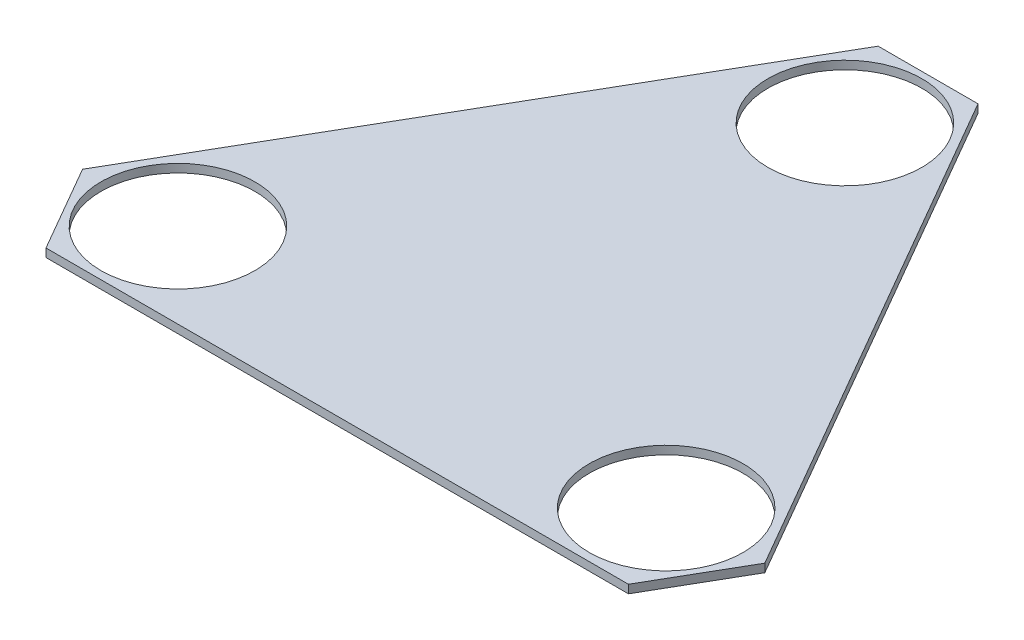
SolidWorks part; units mm, degrees
material "自定义塑料"
ref_plane "前视基准面" through (0, 0, 0) normal (0, 0, 1) x (1, 0, 0)
ref_plane "上视基准面" through (0, 0, 0) normal (0, 1, 0) x (1, 0, 0)
ref_plane "右视基准面" through (0, 0, 0) normal (1, 0, 0) x (0, 0, -1)
sketch "草图1" plane through (0, 0, 0) normal (0, 1, 0) x (1, 0, 0)
  line L0 (0, 0) -> (700, 0)
  line L1 (700, 0) -> (760, 103.923)
  line L2 (760, 103.923) -> (410, 710.1408)
  line L3 (410, 710.1408) -> (290, 710.1408)
  line L4 (290, 710.1408) -> (-60, 103.923)
  line L5 (-60, 103.923) -> (0, 0)
extrude "凸台-拉伸1" add sketch "草图1" along normal blind 10
sketch "草图2" plane through (0, 10, 0) normal (0, 1, 0) x (1, 0, 0)
  line L0 (-30, 51.9615) -> (56.6025, 101.9615)
  line L1 (-60, 103.923) -> (0, 0) construction
  line L2 (730, 51.9615) -> (643.3975, 101.9615)
  line L3 (700, 0) -> (760, 103.923) construction
  line L4 (350, 710.1408) -> (350, 610.1408)
  line L5 (410, 710.1408) -> (290, 710.1408) construction
  circle A0 centre (56.6025, 101.9615) radius 92.5
  circle A1 centre (643.3975, 101.9615) radius 92.5
  circle A2 centre (350, 610.1408) radius 92.5
extrude "切除-拉伸1" cut sketch "草图2" against normal blind 10 contours A2 | A0 | A1
